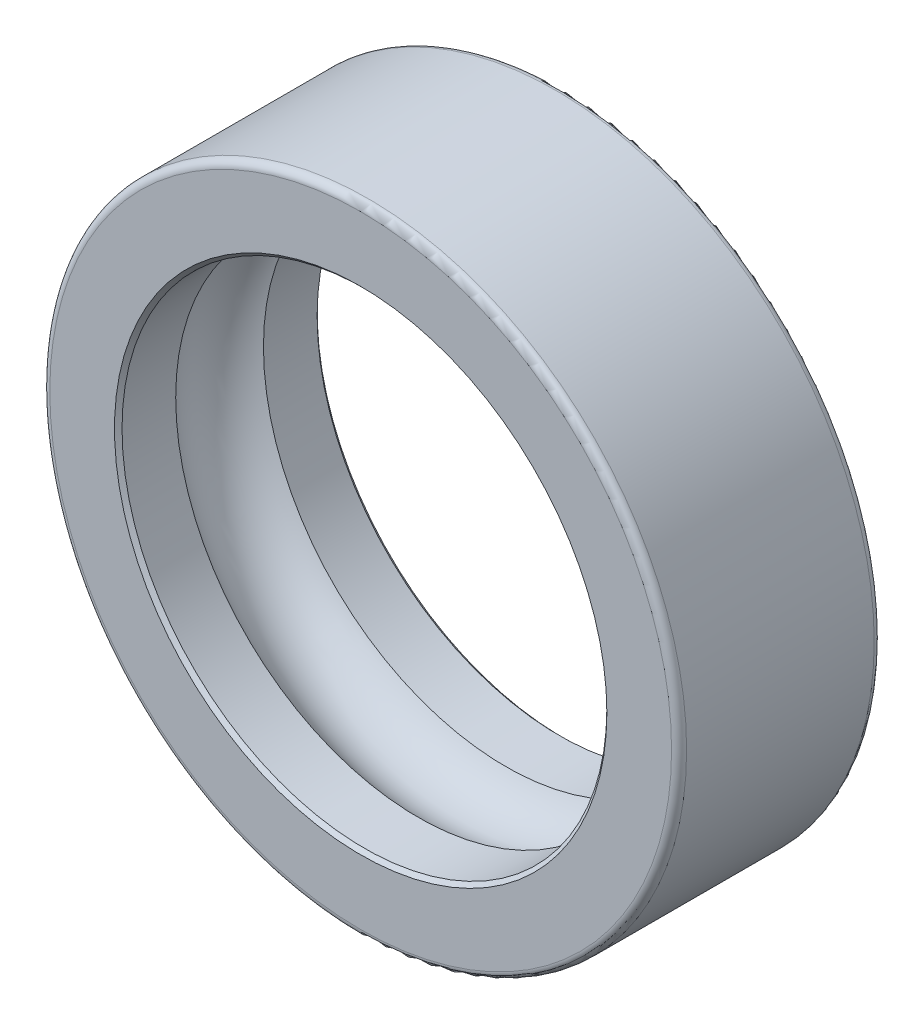
SolidWorks part; units mm, degrees
ref_plane "Front Plane" through (0, 0, 0) normal (0, 0, 1) x (1, 0, 0)
ref_plane "Top Plane" through (0, 0, 0) normal (0, 1, 0) x (1, 0, 0)
ref_plane "Right Plane" through (0, 0, 0) normal (1, 0, 0) x (0, 0, -1)
sketch "Sketch1" plane through (0, 0, 0) normal (1, 0, 0) x (0, 0, -1)
  line L0 (-3.5, 0) -> (3.5, 0) construction
  line L1 (-3.37, 8.375) -> (-1.5155, 8.375)
  line L4 (3.24, 11) -> (-3.24, 11)
  line L7 (3.5, 8.505) -> (3.5, 10.74)
  line L9 (1.5155, 8.375) -> (3.37, 8.375)
  line L10 (-3.5, 8.505) -> (-3.5, 10.74)
  line L11 (-3.5, 8.505) -> (-3.37, 8.375)
  line L14 (3.37, 8.375) -> (3.5, 8.505)
  arc A0 (1.5155, 8.375) -> (-1.5155, 8.375) centre (0, 7.5) ccw
  arc A2 (-3.24, 11) -> (-3.5, 10.74) centre (-3.24, 10.74) ccw
  arc A3 (3.5, 10.74) -> (3.24, 11) centre (3.24, 10.74) ccw
  point P12 (3.5, 8.375)
  point P16 (-3.5, 8.375)
  dimension "D1" = 3.5
  dimension "D6" = 0.26
  dimension "D7" = 0
  dimension "D2" = 7
  dimension "D3" = 3.5
  dimension "D4" = 3.5
  dimension "D5" = 2.625
  dimension "D8" = 0.13
  dimension "D9" = 0.13
  dimension "D10" = 11
  dimension "D14" = 0.13
  dimension "D15" = 0.13
revolve "Revolve1" add sketch "Sketch1" angle 360 about L0
